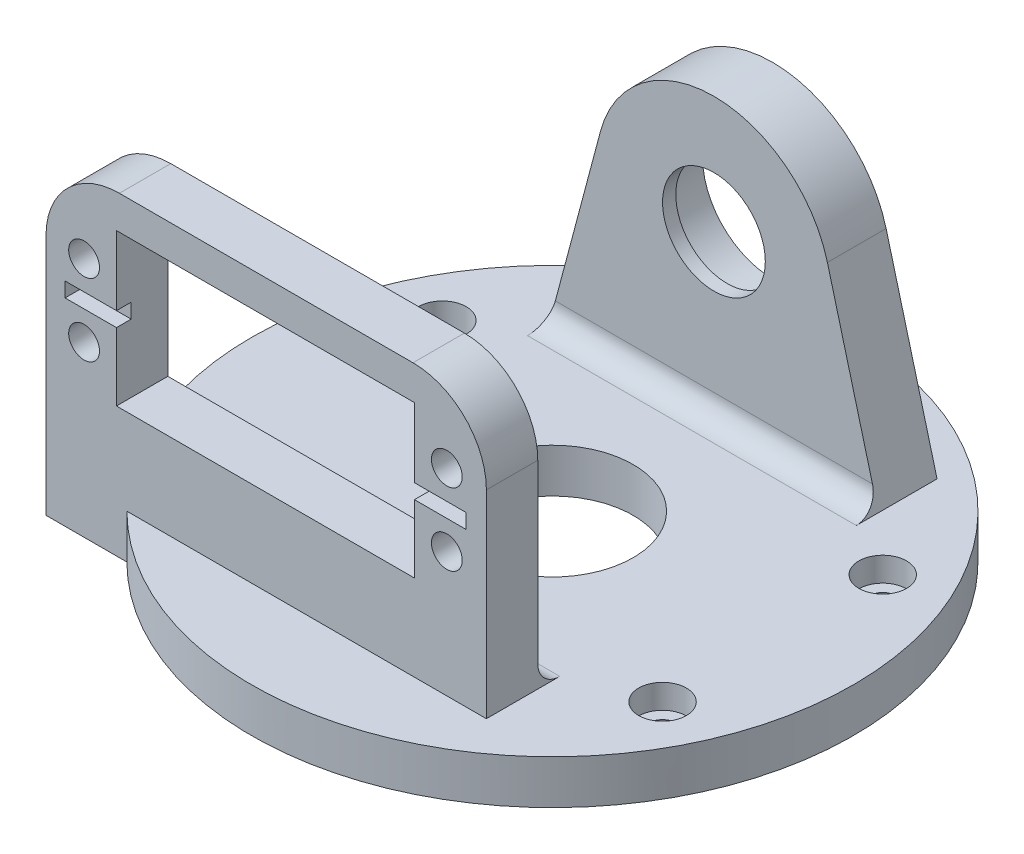
SolidWorks part; units mm, degrees
ref_plane "Front Plane" through (0, 0, 0) normal (0, 0, 1) x (1, 0, 0)
ref_plane "Top Plane" through (0, 0, 0) normal (0, 1, 0) x (1, 0, 0)
ref_plane "Right Plane" through (0, 0, 0) normal (1, 0, 0) x (0, 0, -1)
sketch "Sketch1" plane through (0, 0, 0) normal (0, 1, 0) x (1, 0, 0)
  circle A0 centre (0, 0) radius 41
extrude "Boss-Extrude1" add sketch "Sketch1" along normal blind 6
ref_plane "Plane1" through (0, 0, -30) normal (0, 0, 1) x (1, 0, 0)
sketch "Sketch2" plane through (0, 0, -30) normal (0, 0, 1) x (1, 0, 0)
  line L0 (-24, 0) -> (24, 0)
  line L1 (24, 0) -> (15.4613, 32.067)
  line L2 (-15.4613, 32.067) -> (-24, 0)
  arc A0 (15.4613, 32.067) -> (-15.4613, 32.067) centre (0, 27.95) ccw
extrude "Boss-Extrude2" add sketch "Sketch2" along normal blind 8
ref_plane "Plane2" through (0, 0, 22) normal (0, 0, 1) x (1, 0, 0)
sketch "Sketch3" plane through (0, 0, 22) normal (0, 0, 1) x (1, 0, 0)
  line L0 (-40, 0) -> (20, 0)
  line L1 (20, 0) -> (20, 33)
  line L2 (10, 43) -> (-30, 43)
  line L3 (-40, 33) -> (-40, 0)
  arc A0 (20, 33) -> (10, 43) centre (10, 33) ccw
  arc A1 (-30, 43) -> (-40, 33) centre (-30, 33) ccw
extrude "Boss-Extrude3" add sketch "Sketch3" along normal blind 7
sketch "Sketch4" plane through (0, 0, 22) normal (0, 0, 1) x (1, 0, 0)
  line L1 (-30.4, 17.7) -> (10.2, 17.7)
  line L2 (-30.4, 17.7) -> (-30.4, 38.4)
  line L3 (-30.4, 38.4) -> (10.2, 38.4)
  line L4 (10.2, 17.7) -> (10.2, 38.4)
extrude "Cut-Extrude1" cut sketch "Sketch4" along normal blind 7
sketch "Sketch5" plane through (0, 0, -30) normal (0, 0, 1) x (1, 0, 0)
  circle A0 centre (0, 27.95) radius 9.55
extrude "Cut-Extrude2" cut sketch "Sketch5" along normal blind 6.2
sketch "Sketch6" plane through (0, 0, -30) normal (0, 0, 1) x (1, 0, 0)
  circle A0 centre (0, 27.95) radius 7
extrude "Cut-Extrude3" cut sketch "Sketch6" along normal blind 8
sketch "Sketch7" plane through (0, 0, 0) normal (0, 1, 0) x (1, 0, 0)
  circle A0 centre (0, 0) radius 11
  circle A1 centre (30, 15) radius 1.7
  circle A2 centre (30, -15) radius 1.7
  circle A3 centre (-30, 15) radius 1.7
  circle A4 centre (-30, -15) radius 1.7
extrude "Cut-Extrude4" cut sketch "Sketch7" along normal blind 6
sketch "Sketch8" plane through (0, 6, 0) normal (0, 1, 0) x (1, 0, 0)
  circle A0 centre (30, 15) radius 3.25
  circle A1 centre (30, -15) radius 3.25
  circle A2 centre (-30, 15) radius 3.25
  circle A3 centre (-30, -15) radius 3.25
extrude "Cut-Extrude6" cut sketch "Sketch8" against normal blind 3.3
sketch "Sketch10" plane through (0, 0, 29) normal (0, 0, 1) x (1, 0, 0)
  circle A0 centre (-34.811, 23.025) radius 2.1
  circle A1 centre (-34.811, 32.875) radius 2.1
  circle A2 centre (14.611, 23.025) radius 2.1
  circle A3 centre (14.611, 32.875) radius 2.1
extrude "Cut-Extrude8" cut sketch "Sketch10" against normal blind 5.5
fillet "Fillet1" radius 3 2 edges at (0, 6, -22) (-7.2988, 6, 22)
chamfer "Chamfer1" distance 0.8 angle 45 4 edges at (-30, 0, 16.7) (-30, 0, -13.3) (30, 0, 16.7) (30, 0, -13.3)
ref_plane "Plane3" through (0, 0, 29) normal (0, 0, 1) x (1, 0, 0)
sketch "Sketch11" plane through (0, 0, 29) normal (0, 0, 1) x (1, 0, 0)
  line L1 (-37.4, 26.95) -> (-30.2, 26.95)
  line L2 (-37.4, 26.95) -> (-37.4, 28.95)
  line L3 (-37.4, 28.95) -> (-30.2, 28.95)
  line L4 (-30.2, 26.95) -> (-30.2, 28.95)
  line L6 (10, 26.95) -> (17.2, 26.95)
  line L7 (10, 26.95) -> (10, 28.95)
  line L8 (10, 28.95) -> (17.2, 28.95)
  line L9 (17.2, 26.95) -> (17.2, 28.95)
extrude "Cut-Extrude9" cut sketch "Sketch11" against normal blind 2
